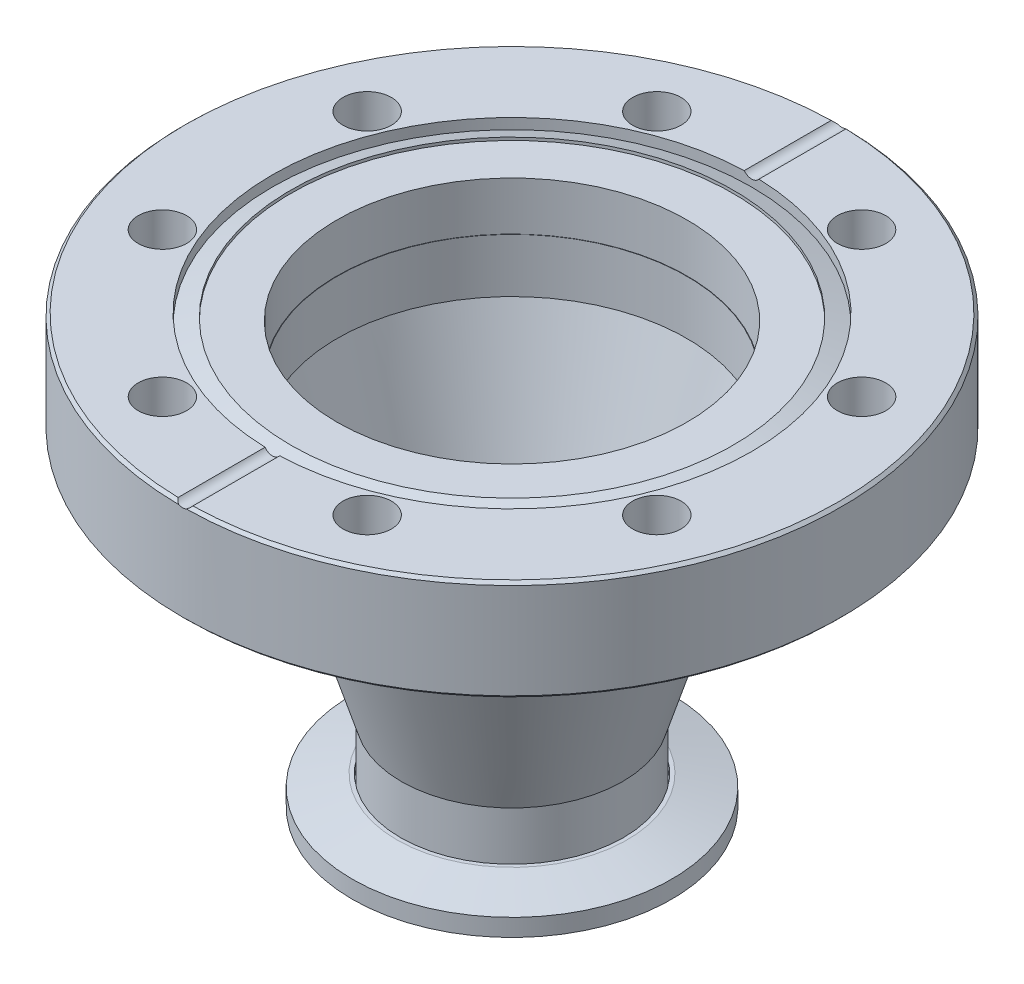
SolidWorks part; units mm, degrees
ref_plane "Front Plane" through (0, 0, 0) normal (0, 0, 1) x (1, 0, 0)
ref_plane "Top Plane" through (0, 0, 0) normal (0, 1, 0) x (1, 0, 0)
ref_plane "Right Plane" through (0, 0, 0) normal (1, 0, 0) x (0, 0, -1)
sketch "Sketch1" plane through (0, 0, 0) normal (1, 0, 0) x (0, 0, -1)
  line L0 (0, 36.83) -> (0, -36.83) construction
  line L1 (0, -36.83) -> (27.5, -36.83)
  line L2 (27.5, -36.83) -> (27.5, -33.83)
  line L3 (27.5, -33.83) -> (19.8493, -31.78)
  line L4 (19.8493, -31.78) -> (0, -31.78)
  line L6 (19.2, -33.02) -> (18.3, -33.02)
  line L7 (18.3, -33.02) -> (18.3, -36.83)
  line L9 (20.5, -34.33) -> (20.5, -36.83)
  line L10 (19.2, -33.02) -> (19.2, -31.78)
  line L11 (20.5, -34.33) -> (18.3, -34.33)
  point P2 (0, 0)
  dimension "D1" = 38.4
  dimension "Length" = 73.66
  dimension "Flange OD (Quick Clamp Tube Connection)" = 55
  dimension "D2" = 3
  dimension "D3" = 3.81
  dimension "D4" = 36.6
  dimension "D5" = 5.05
  dimension "D6" = 2.5
  dimension "D8" = 75
  dimension "D9" = 41
sketch "Sketch2" plane through (0, 0, 0) normal (1, 0, 0) x (0, 0, -1)
  line L0 (0, 36.83) -> (0, -36.83) construction
  line L1 (0, 36.83) -> (0, -36.83) construction
  line L2 (19.05, -33.02) -> (19.05, -23.495)
  line L3 (19.2, -33.02) -> (18.3, -33.02) construction
  line L4 (19.05, -23.495) -> (31.75, 17.78)
  line L5 (31.75, 17.78) -> (31.75, 27.305)
  line L6 (17.399, -33.02) -> (17.399, -23.2467)
  line L7 (17.399, -23.2467) -> (30.099, 18.0283)
  line L8 (30.099, 18.0283) -> (30.099, 27.305)
  line L9 (17.399, -33.02) -> (19.05, -33.02)
  line L10 (30.099, 27.305) -> (31.75, 27.305)
  dimension "D1" = 60.325
  dimension "D2" = 9.525
  dimension "D3" = 9.525
  dimension "D5" = 63.5
  dimension "D6" = 38.1
  dimension "D4" = 1.651
sketch "Sketch3" plane through (0, 0, 0) normal (1, 0, 0) x (0, 0, -1)
  line L0 (0, 36.83) -> (0, -36.83) construction
  line L1 (0, 36.83) -> (0, -36.83) construction
  line L2 (0, 36.83) -> (56.7436, 36.83)
  line L3 (56.7436, 36.83) -> (56.7436, 19.3802)
  line L4 (56.7436, 19.3802) -> (0, 19.3802)
  line L5 (41.275, 36.83) -> (41.275, 35.0047)
  line L6 (41.275, 35.0047) -> (38.0746, 36.1696)
  line L7 (38.0746, 36.1696) -> (38.0746, 35.6616)
  line L8 (38.0746, 35.6616) -> (30.1625, 35.6616)
  line L9 (30.1625, 35.6616) -> (30.1625, 27.305)
  line L10 (30.1625, 27.305) -> (31.75, 27.305)
  line L11 (31.75, 27.305) -> (31.75, 19.3802)
  line L12 (30.099, 27.305) -> (31.75, 27.305) construction
  line L13 (56.2436, 36.83) -> (56.7436, 36.33)
  line L14 (56.2436, 19.3802) -> (56.7436, 19.8802)
  dimension "D1" = 17.4498
  dimension "D2" = 82.55
  dimension "Flange OD (Flanged Tube Connection)" = 113.4872
  dimension "D3" = 70
  dimension "D4" = 76.1492
  dimension "D5" = 0.508
  dimension "D6" = 1.1684
  dimension "D7" = 60.325
  dimension "D8" = 63.5
  dimension "D9" = 45
  dimension "D10" = 0.5
sketch "Sketch4" plane through (0, 0, 0) normal (0, 1, 0) x (1, 0, 0)
  line L0 (0, 0) -> (17.6321, 42.5677) construction
  line L1 (0, 0) -> (0, 46.075) construction
  line L2 (0, 0) -> (-17.6321, 42.5677) construction
  circle A0 centre (0, 0) radius 56.7436
  circle A1 centre (0, 0) radius 46.075
  circle A2 centre (17.6321, 42.5677) radius 4.1672
  circle A3 centre (17.6321, 42.5677) radius 3.9688
  dimension "D1" = 45
  dimension "Bolt Circle Diameter" = 92.15
  dimension "Bolt Hole Diameter" = 8.3344
  dimension "For Bolt Diameter" = 7.9375
sketch "Sketch5" plane through (0, 0, 0) normal (1, 0, 0) x (0, 0, -1)
  line L0 (20.5, -34.33) -> (20.5, -36.83) construction
  line L2 (18.3, -33.02) -> (18.3, -36.83) construction
  line L3 (19.2, -33.02) -> (18.3, -33.02) construction
  line L5 (20.5, -34.33) -> (20.5, -36.83)
  line L7 (18.3, -33.02) -> (18.3, -34.33)
  line L8 (19.2, -33.02) -> (18.3, -33.02)
  line L10 (0, -36.83) -> (27.5, -36.83) construction
  line L11 (27.5, -36.83) -> (27.5, -33.83) construction
  line L12 (27.5, -33.83) -> (19.8493, -31.78) construction
  line L13 (20.5, -36.83) -> (27.5, -36.83)
  line L14 (27.5, -36.83) -> (27.5, -33.83)
  line L15 (27.5, -33.83) -> (19.8493, -31.78)
  line L16 (0, 36.83) -> (0, -36.83) construction
  line L17 (0, 36.83) -> (0, -36.83) construction
  line L18 (19.2, -33.02) -> (19.2, -31.78) construction
  line L19 (19.2, -33.02) -> (19.2, -31.78)
  line L21 (20.5, -34.33) -> (18.3, -34.33) construction
  line L23 (20.5, -34.33) -> (18.3, -34.33)
  line L24 (19.2, -31.78) -> (19.8493, -31.78)
revolve "Revolve1" add sketch "Sketch5" angle 360 about L17
sketch "Sketch6" plane through (0, 0, 0) normal (1, 0, 0) x (0, 0, -1)
  line L0 (0, 36.83) -> (0, -36.83) construction
  line L1 (0, 36.83) -> (0, -36.83) construction
  line L2 (17.399, -33.02) -> (17.399, -23.2467) construction
  line L3 (17.399, -33.02) -> (19.05, -33.02) construction
  line L4 (19.05, -33.02) -> (19.05, -23.495) construction
  line L5 (19.05, -23.495) -> (31.75, 17.78) construction
  line L6 (31.75, 17.78) -> (31.75, 27.305) construction
  line L7 (30.099, 27.305) -> (31.75, 27.305) construction
  line L8 (30.099, 18.0283) -> (30.099, 27.305) construction
  line L9 (17.399, -23.2467) -> (30.099, 18.0283) construction
  line L10 (17.399, -33.02) -> (17.399, -23.2467)
  line L11 (17.399, -33.02) -> (19.05, -33.02)
  line L12 (19.05, -33.02) -> (19.05, -23.495)
  line L13 (19.05, -23.495) -> (31.75, 17.78)
  line L14 (31.75, 17.78) -> (31.75, 27.305)
  line L15 (30.099, 27.305) -> (31.75, 27.305)
  line L16 (30.099, 18.0283) -> (30.099, 27.305)
  line L17 (17.399, -23.2467) -> (30.099, 18.0283)
revolve "Revolve2" add sketch "Sketch6" angle 360 about L1
sketch "Sketch7" plane through (0, 0, 0) normal (1, 0, 0) x (0, 0, -1)
  line L0 (31.75, 27.305) -> (31.75, 19.3802) construction
  line L1 (30.1625, 27.305) -> (31.75, 27.305) construction
  line L2 (30.1625, 35.6616) -> (30.1625, 27.305) construction
  line L3 (38.0746, 35.6616) -> (30.1625, 35.6616) construction
  line L4 (38.0746, 36.1696) -> (38.0746, 35.6616) construction
  line L5 (41.275, 35.0047) -> (38.0746, 36.1696) construction
  line L6 (41.275, 36.83) -> (41.275, 35.0047) construction
  line L7 (31.75, 27.305) -> (31.75, 19.3802)
  line L8 (30.1625, 27.305) -> (31.75, 27.305)
  line L9 (30.1625, 35.6616) -> (30.1625, 27.305)
  line L10 (38.0746, 35.6616) -> (30.1625, 35.6616)
  line L11 (38.0746, 36.1696) -> (38.0746, 35.6616)
  line L12 (41.275, 35.0047) -> (38.0746, 36.1696)
  line L13 (41.275, 36.83) -> (41.275, 35.0047)
  line L14 (56.2436, 36.83) -> (56.7436, 36.33) construction
  line L15 (56.2436, 19.3802) -> (56.7436, 19.8802) construction
  line L16 (56.2436, 36.83) -> (56.7436, 36.33)
  line L17 (56.2436, 19.3802) -> (56.7436, 19.8802)
  line L18 (0, 36.83) -> (56.7436, 36.83) construction
  line L19 (56.7436, 19.3802) -> (0, 19.3802) construction
  line L20 (56.7436, 36.83) -> (56.7436, 19.3802) construction
  line L21 (41.275, 36.83) -> (56.2436, 36.83)
  line L22 (56.2436, 19.3802) -> (31.75, 19.3802)
  line L23 (56.7436, 36.33) -> (56.7436, 19.8802)
  line L24 (0, 36.83) -> (0, -36.83) construction
  line L25 (0, 36.83) -> (0, -36.83) construction
revolve "Revolve3" add sketch "Sketch7" angle 360 about L25
sketch "Sketch8" plane through (0, 36.83, 0) normal (0, 1, 0) x (1, 0, 0)
  circle A0 centre (17.6321, 42.5677) radius 4.1672 construction
  circle A1 centre (17.6321, 42.5677) radius 4.1672
extrude "Cut-Extrude1" cut sketch "Sketch8" against normal through all
pattern_circular "CirPattern1" count 8 over 360 about axis through (0, 0, 0) along (0, 1, 0) of "Cut-Extrude1"
sketch "Sketch9" plane through (0, 0, 0) normal (0, 0, 1) x (1, 0, 0)
  line L0 (0, 36.83) -> (0, 37.7825) construction
  line L1 (56.2436, 36.83) -> (-56.2436, 36.83) construction
  line L2 (-1.27, 36.83) -> (1.27, 36.83) construction
  line L3 (41.275, 36.83) -> (-41.275, 36.83) construction
  circle A0 centre (0, 37.7825) radius 1.5875
  dimension "D1" = 3.175
  dimension "D2" = 0.9525
extrude "Cut-Extrude2" cut sketch "Sketch9" against normal through all both and the other way through all
